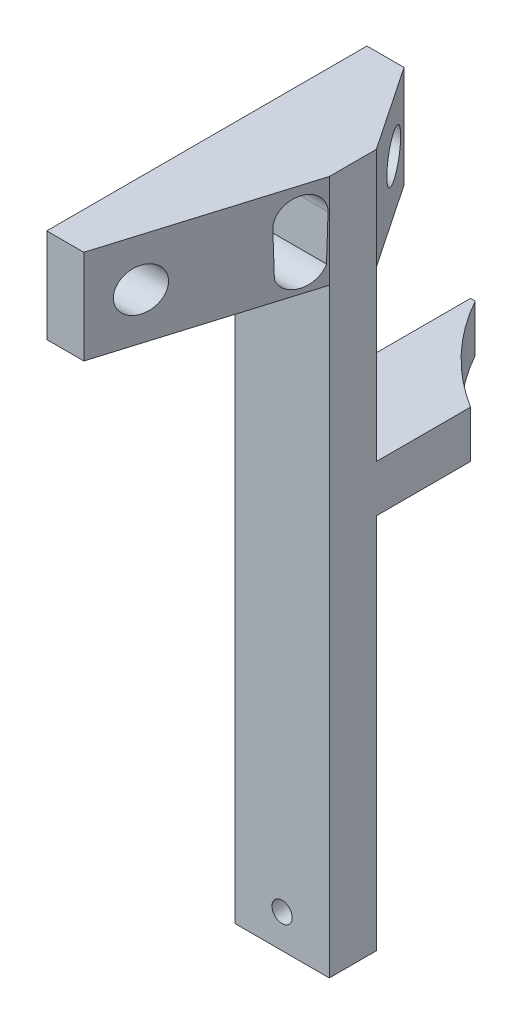
SolidWorks part; units mm, degrees
ref_plane "前视基准面" through (0, 0, 0) normal (0, 0, 1) x (1, 0, 0)
ref_plane "上视基准面" through (0, 0, 0) normal (0, 1, 0) x (1, 0, 0)
ref_plane "右视基准面" through (0, 0, 0) normal (1, 0, 0) x (0, 0, -1)
sketch "草图1" plane through (0, 0, 0) normal (0, 0, 1) x (1, 0, 0)
  line L0 (20.0138, -131.8034) -> (20.0138, 15.6116) construction
  line L7 (10.0138, 15.6116) -> (30.0138, 15.6116)
  line L8 (10.0138, 15.6116) -> (10.0138, -131.8034)
  line L9 (10.0138, -131.8034) -> (30.0138, -131.8034)
  line L10 (30.0138, 15.6116) -> (30.0138, -131.8034)
  circle A0 centre (20, -124.6534) radius 2.15
  dimension "D1" = 4.3
  dimension "D4" = 147.415
  dimension "D5" = 7.15
  dimension "D6" = 20
extrude "凸台-拉伸1" add sketch "草图1" along normal blind 10
sketch "草图2" plane through (0, 0, 10) normal (0, 0, 1) x (1, 0, 0)
  line L0 (30.0138, -131.8034) -> (30.0138, 15.6116) construction
  line L1 (10.0138, 15.6116) -> (30.0138, 15.6116)
  line L2 (10.0138, 15.6116) -> (10.0138, -4.3884)
  line L3 (10.0138, -4.3884) -> (30.0138, -4.3884)
  line L4 (30.0138, 15.6116) -> (30.0138, -4.3884)
  dimension "D1" = 20
extrude "凸台-拉伸2" add sketch "草图2" along normal blind 40
sketch "草图3" plane through (0, 0, 0) normal (0, 0, -1) x (-1, 0, 0)
  line L0 (-10.0138, 15.6116) -> (-10.0138, -131.8034) construction
  line L1 (-30.0138, 15.6116) -> (-10.0138, 15.6116)
  line L2 (-30.0138, 15.6116) -> (-30.0138, -6.0242)
  line L3 (-30.0138, -6.0242) -> (-10.0138, -6.0242)
  line L4 (-10.0138, 15.6116) -> (-10.0138, -6.0242)
extrude "凸台-拉伸3" add sketch "草图3" along normal blind 18
sketch "草图4" plane through (0, -4.3884, 0) normal (0, -1, 0) x (1, 0, 0)
  line L0 (17.8938, 50) -> (30.0138, 50)
  line L1 (10.0138, 50) -> (30.0138, 50) construction
  line L2 (30.0138, 50) -> (30.0138, 10)
  line L3 (30.0138, 10) -> (17.8938, 50)
  line L4 (10.0138, 50) -> (10.0138, 10) construction
  line L5 (17.8938, -18) -> (30.0138, -18)
  line L6 (30.0138, -18) -> (10.0138, -18) construction
  line L7 (30.0138, -18) -> (30.0138, 0)
  line L8 (30.0138, 0) -> (17.8938, -18)
  line L9 (10.0138, -18) -> (10.0138, 0) construction
  dimension "D1" = 7.88
  dimension "D2" = 7.88
extrude "切除-拉伸1" cut sketch "草图4" against normal blind 20 and the other way blind 10
sketch "草图5" plane through (10.0138, 0, 0) normal (-1, 0, 0) x (0, 0, 1)
  line L0 (10, -49.2013) -> (10, 38.8132) construction
  line L1 (10, -4.3884) -> (10, -131.8034) construction
  line L2 (50, 5.6116) -> (-18, 4.7937) construction
  line L3 (50, 15.6116) -> (50, -4.3884) construction
  line L4 (-18, -6.0242) -> (-18, 15.6116) construction
  circle A0 centre (14.7, 9.1873) radius 2.15
  circle A1 centre (14.7, 1.1873) radius 2.15
  circle A2 centre (40.7, 5.4997) radius 2.15
  circle A3 centre (-11.3, 4.8743) radius 2.15
  dimension "D1" = 4.3
  dimension "D2" = 4.3
  dimension "D7" = 4.3
  dimension "D8" = 4.3
  dimension "D3" = 8
  dimension "D4" = 4
  dimension "D5" = 4.7
  dimension "D6" = 4.7
  dimension "D9" = 26
  dimension "D10" = 26
extrude "切除-拉伸2" cut sketch "草图5" against normal blind 2
sketch "草图6" plane through (10.0138, 0, 0) normal (-1, 0, 0) x (0, 0, 1)
  line L0 (19.2, 9.1873) -> (18.9423, -0.3137)
  line L1 (10.2, 9.1873) -> (10.4577, -0.3137)
  arc A0 (19.2, 9.1873) -> (10.2, 9.1873) centre (14.7, 9.1873) ccw
  arc A1 (10.4577, -0.3137) -> (18.9423, -0.3137) centre (14.7, 1.1873) ccw
  circle A2 centre (40.7, 5.4997) radius 4.5
  circle A3 centre (-11.3, 4.8743) radius 4.5
  dimension "D1" = 9
  dimension "D2" = 9
  dimension "D3" = 9
  dimension "D4" = 9
extrude "切除-拉伸3" cut sketch "草图6" against normal blind 20 from offset 2 offset against normal yes
sketch "草图7" plane through (0, 0, 0) normal (0, 0, -1) x (-1, 0, 0)
  line L0 (-30.0138, -131.8034) -> (-30.0138, -6.0242) construction
  line L1 (-30.0138, -41.8034) -> (-10.0138, -41.8034)
  line L2 (-30.0138, -41.8034) -> (-30.0138, -51.8034)
  line L3 (-30.0138, -51.8034) -> (-10.0138, -51.8034)
  line L4 (-10.0138, -41.8034) -> (-10.0138, -51.8034)
  line L5 (-10.0138, -6.0242) -> (-10.0138, -131.8034) construction
  line L6 (-10.0138, -131.8034) -> (-30.0138, -131.8034) construction
  dimension "D1" = 80
  dimension "D2" = 10
extrude "凸台-拉伸4" add sketch "草图7" along normal blind 40
sketch "草图8" plane through (0, -41.8034, 0) normal (0, 1, 0) x (1, 0, 0)
  line L2 (30.0138, 40) -> (30.0138, 0) construction
  line L3 (10.0138, 40) -> (30.0138, 40) construction
  line L4 (30.0138, 20) -> (30.0138, 40)
  line L5 (30.0138, 40) -> (11.0138, 40)
  arc A0 (11.0138, 40) -> (30.0138, 20) centre (59.1145, 66.6707) ccw
  dimension "D1" = 110
  dimension "D2" = 20
  dimension "D3" = 19
extrude "切除-拉伸5" cut sketch "草图8" against normal up to next
